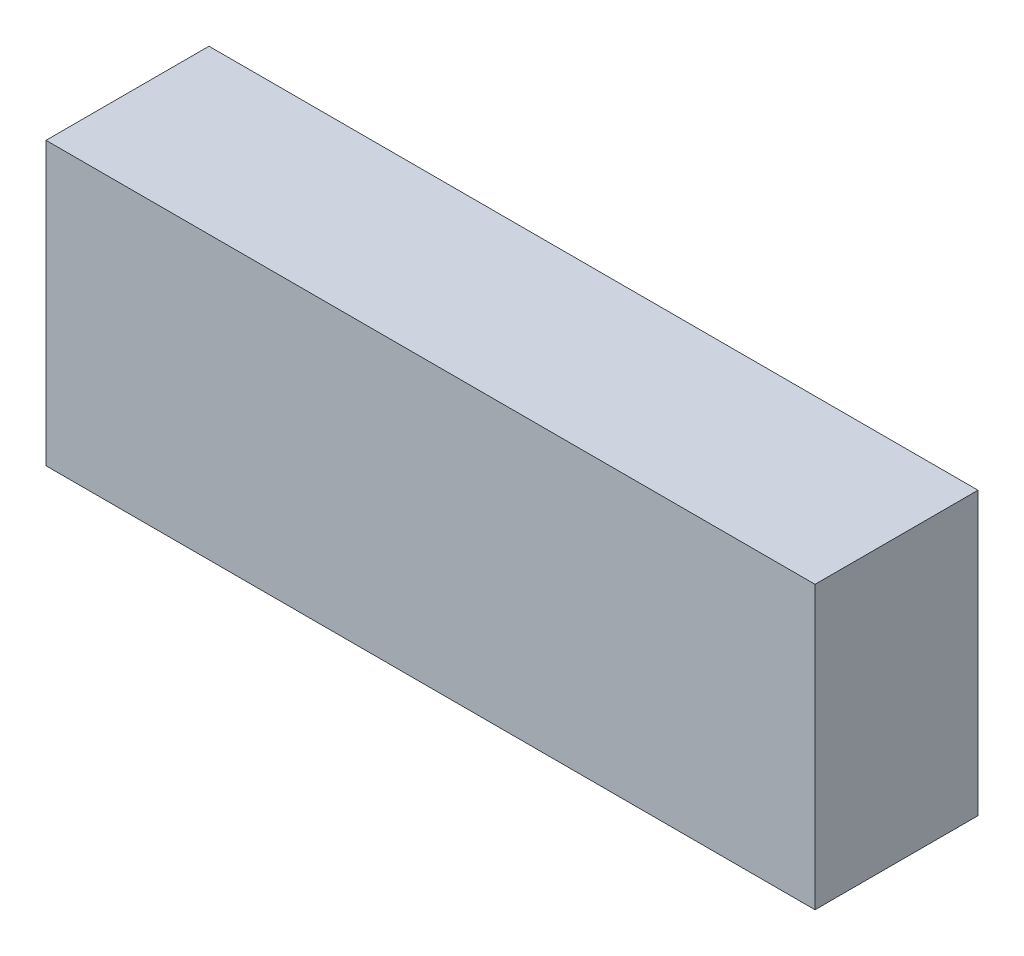
SolidWorks part; units mm, degrees
ref_plane "Front Plane" through (0, 0, 0) normal (0, 0, 1) x (1, 0, 0)
ref_plane "Top Plane" through (0, 0, 0) normal (0, 1, 0) x (1, 0, 0)
ref_plane "Right Plane" through (0, 0, 0) normal (1, 0, 0) x (0, 0, -1)
sketch "Sketch1" plane through (0, 0, 0) normal (0, 0, 1) x (1, 0, 0)
  line L0 (44.6245, -1.49) -> (79.2368, -1.49) construction
  line L1 (44.8245, -1.69) -> (79.0368, -1.69)
  line L2 (44.8245, -1.69) -> (44.8245, -14.23)
  line L3 (44.8245, -14.23) -> (79.0368, -14.23)
  line L4 (79.0368, -1.69) -> (79.0368, -14.23)
  line L5 (79.2368, -14.43) -> (79.2368, -1.49) construction
  line L6 (79.2368, -14.43) -> (44.6245, -14.43) construction
  line L7 (44.6245, -14.43) -> (44.6245, -1.49) construction
  dimension "D1" = 0.2
  dimension "D2" = 0.2
  dimension "D3" = 0.2
  dimension "D4" = 0.2
extrude "Boss-Extrude1" add sketch "Sketch1" along normal blind 7.25
shell "Shell1" thickness 0.5
equation "\"D2@Sketch1\"=\"D1@Sketch1\""
equation "\"D3@Sketch1\"=\"D1@Sketch1\""
equation "\"D4@Sketch1\"=\"D1@Sketch1\""
